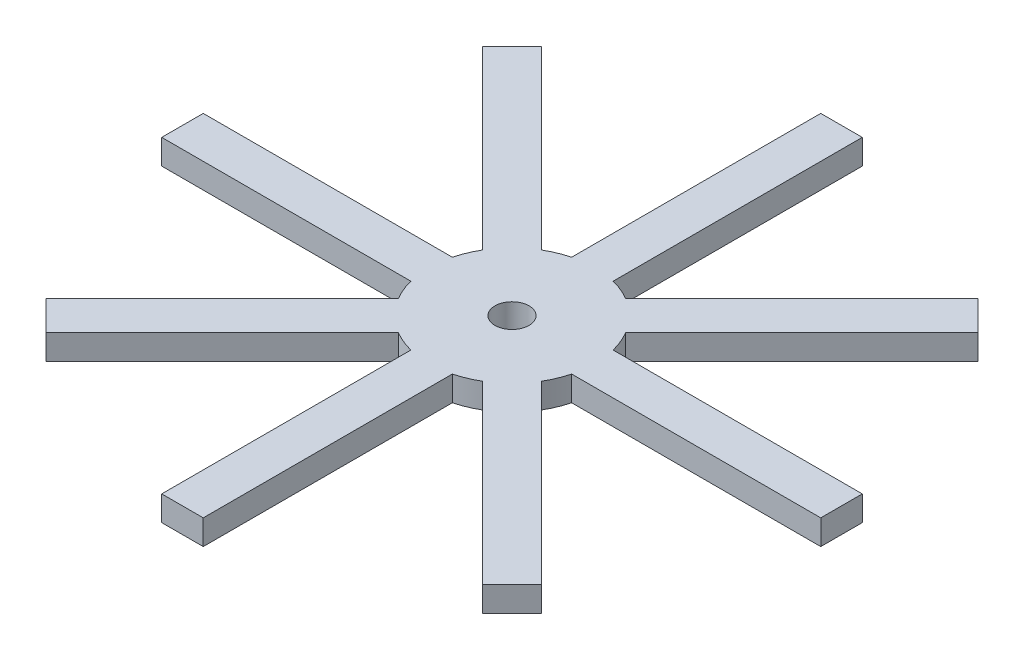
SolidWorks part; units mm, degrees
ref_plane "Plano frontal" through (0, 0, 0) normal (0, 0, 1) x (1, 0, 0)
ref_plane "Plano superior" through (0, 0, 0) normal (0, 1, 0) x (1, 0, 0)
ref_plane "Plano direito" through (0, 0, 0) normal (1, 0, 0) x (0, 0, -1)
sketch "Esboço1" plane through (0, 0, 0) normal (0, 1, 0) x (1, 0, 0)
  circle A0 centre (0, 0) radius 20
  circle A1 centre (0, 0) radius 4.1
  dimension "D1" = 40
  dimension "D2" = 8.2
extrude "Ressalto-extrusão1" add sketch "Esboço1" along normal blind 6
sketch "Esboço2" plane through (0, 6, 0) normal (0, 1, 0) x (1, 0, 0)
  line L0 (52.5839, 59.655) -> (59.655, 52.5839)
  line L1 (-5, 79.3649) -> (5, 79.3649)
  line L2 (-5, 79.3649) -> (-5, 19.3649)
  line L3 (-5, 19.3649) -> (5, 19.3649)
  line L4 (5, 79.3649) -> (5, 19.3649)
  line L5 (52.5839, 59.655) -> (10.1575, 17.2286)
  line L6 (10.1575, 17.2286) -> (17.2286, 10.1575)
  line L7 (59.655, 52.5839) -> (17.2286, 10.1575)
  line L8 (79.3649, 5) -> (79.3649, -5)
  line L9 (79.3649, 5) -> (19.3649, 5)
  line L10 (19.3649, 5) -> (19.3649, -5)
  line L11 (79.3649, -5) -> (19.3649, -5)
  line L12 (59.655, -52.5839) -> (52.5839, -59.655)
  line L13 (59.655, -52.5839) -> (17.2286, -10.1575)
  line L14 (17.2286, -10.1575) -> (10.1575, -17.2286)
  line L15 (52.5839, -59.655) -> (10.1575, -17.2286)
  line L16 (5, -79.3649) -> (-5, -79.3649)
  line L17 (5, -79.3649) -> (5, -19.3649)
  line L18 (5, -19.3649) -> (-5, -19.3649)
  line L19 (-5, -79.3649) -> (-5, -19.3649)
  line L20 (-52.5839, -59.655) -> (-59.655, -52.5839)
  line L21 (-52.5839, -59.655) -> (-10.1575, -17.2286)
  line L22 (-10.1575, -17.2286) -> (-17.2286, -10.1575)
  line L23 (-59.655, -52.5839) -> (-17.2286, -10.1575)
  line L24 (-79.3649, -5) -> (-79.3649, 5)
  line L25 (-79.3649, -5) -> (-19.3649, -5)
  line L26 (-19.3649, -5) -> (-19.3649, 5)
  line L27 (-79.3649, 5) -> (-19.3649, 5)
  line L28 (-59.655, 52.5839) -> (-52.5839, 59.655)
  line L29 (-59.655, 52.5839) -> (-17.2286, 10.1575)
  line L30 (-17.2286, 10.1575) -> (-10.1575, 17.2286)
  line L31 (-52.5839, 59.655) -> (-10.1575, 17.2286)
  circle A0 centre (0, 0) radius 20 construction
  point P37 (0, 0)
  dimension "D1" = 60
  dimension "D2" = 10
  dimension "D3" = 8
extrude "Ressalto-extrusão2" add sketch "Esboço2" against normal blind 6
